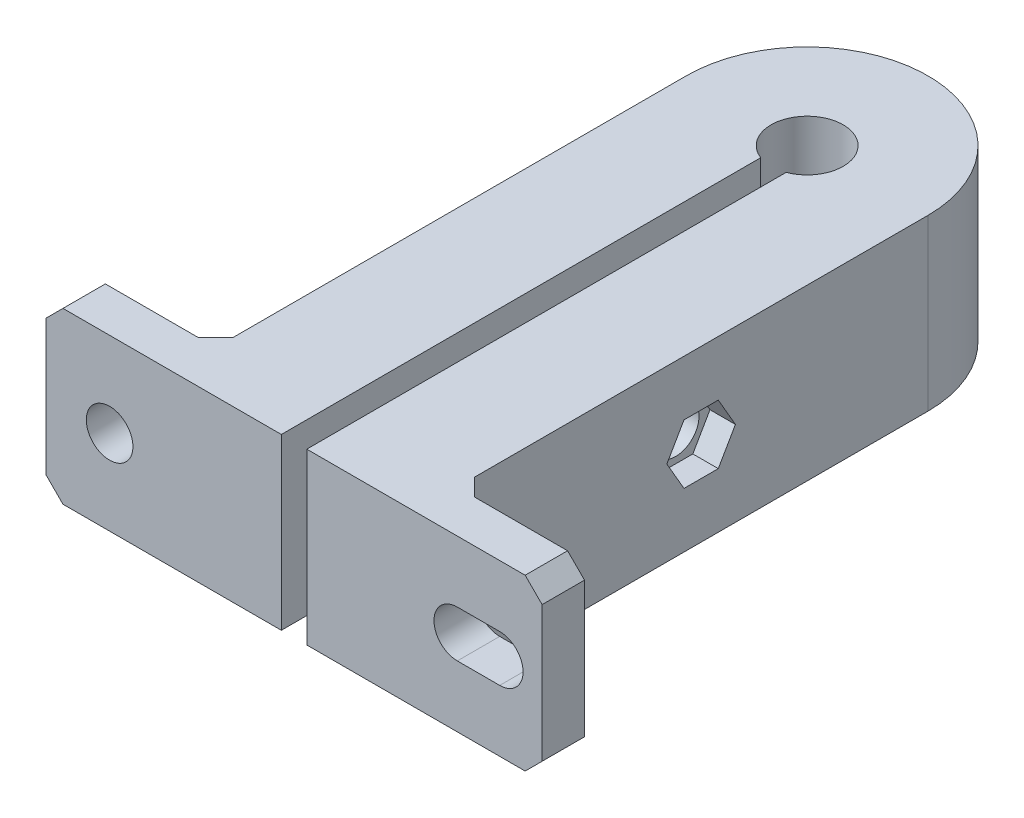
SolidWorks part; units mm, degrees
ref_plane "Front Plane" through (0, 0, 0) normal (0, 0, 1) x (1, 0, 0)
ref_plane "Top Plane" through (0, 0, 0) normal (0, 1, 0) x (1, 0, 0)
ref_plane "Right Plane" through (0, 0, 0) normal (1, 0, 0) x (0, 0, -1)
sketch "Sketch1" plane through (0, 0, 0) normal (0, 1, 0) x (1, 0, 0)
  line L0 (-14.25, 0) -> (-14.25, -60.5)
  line L1 (-14.25, -60.5) -> (14.25, -60.5)
  line L2 (14.25, -60.5) -> (14.25, 0)
  circle A0 centre (0, 0) radius 4.25
  arc A1 (14.25, 0) -> (-14.25, 0) centre (0, 0) ccw
  dimension "D1" = 8.5
  dimension "D2" = 10
  dimension "D3" = 60.5
extrude "Boss-Extrude1" add sketch "Sketch1" along normal blind 20
sketch "Sketch3" plane through (0, 20, 0) normal (0, 1, 0) x (1, 0, 0)
  line L0 (0, -60.5) -> (0, 0)
  line L1 (-14.25, -60.5) -> (14.25, -60.5) construction
extrude "Cut-Extrude-Thin1" cut sketch "Sketch3" against normal blind 20 and the other way through all thin thin type mid plane wall 3
sketch "Sketch4" plane through (0, 0, 60.5) normal (0, 0, 1) x (1, 0, 0)
  line L0 (-14.25, 20) -> (-14.25, 0) construction
  line L1 (-1.5, 0) -> (-29.25, 0)
  line L2 (-1.5, 0) -> (-1.5, 20)
  line L3 (-1.5, 20) -> (-29.25, 20)
  line L4 (-29.25, 0) -> (-29.25, 20)
  dimension "D1" = 15
extrude "Boss-Extrude2" add sketch "Sketch4" against normal blind 5
mirror "Mirror1" about plane through (0, 0, 0) normal (1, 0, 0) of "Boss-Extrude2"
sketch "Sketch5" plane through (0, 0, 55.5) normal (0, 0, -1) x (-1, 0, 0)
  line L0 (14.25, 20) -> (29.25, 0) construction
  line L1 (-29.25, 20) -> (-14.25, 0) construction
  line L2 (-24.25, 10) -> (-19.25, 10) construction
  line L3 (-24.25, 12.75) -> (-19.25, 12.75)
  line L4 (-24.25, 7.25) -> (-19.25, 7.25)
  circle A0 centre (21.75, 10) radius 2.75
  arc A1 (-24.25, 12.75) -> (-24.25, 7.25) centre (-24.25, 10) ccw
  arc A2 (-19.25, 7.25) -> (-19.25, 12.75) centre (-19.25, 10) ccw
  point P12 (-21.75, 10)
  dimension "D1" = 5.5
  dimension "D2" = 2.75
  dimension "D3" = 5
extrude "Cut-Extrude1" cut sketch "Sketch5" against normal blind 5
chamfer "Chamfer1" distance 2 angle 45 2 edges at (-14.25, 10, 55.5) (14.25, 10, 55.5)
chamfer "Chamfer2" distance 2 angle 45 4 edges at (29.25, 0, 58) (29.25, 20, 58) (-29.25, 0, 58) (-29.25, 20, 58)
sketch "Sketch6" plane through (14.25, 0, 0) normal (1, 0, 0) x (0, 0, -1)
  line L0 (-53.5, 20) -> (0, 0) construction
  circle A0 centre (-26.75, 10) radius 2.75
  dimension "D1" = 5.5
extrude "Cut-Extrude2" cut sketch "Sketch6" against normal blind 35
sketch "Sketch7" plane through (14.25, 0, 0) normal (1, 0, 0) x (0, 0, -1)
  line L1 (-22.7085, 10) -> (-24.7293, 13.5)
  line L2 (-24.7293, 13.5) -> (-28.7707, 13.5)
  line L3 (-28.7707, 13.5) -> (-30.7915, 10)
  line L4 (-30.7915, 10) -> (-28.7707, 6.5)
  line L5 (-28.7707, 6.5) -> (-24.7293, 6.5)
  line L6 (-24.7293, 6.5) -> (-22.7085, 10)
  circle A0 centre (-26.75, 10) radius 3.5 construction
  dimension "D1" = 7
extrude "Cut-Extrude3" cut sketch "Sketch7" against normal blind 3
sketch "Sketch8" plane through (-14.25, 0, 0) normal (-1, 0, 0) x (0, 0, 1)
  circle A0 centre (26.75, 10) radius 4
  dimension "D1" = 8
extrude "Cut-Extrude4" cut sketch "Sketch8" against normal blind 4
